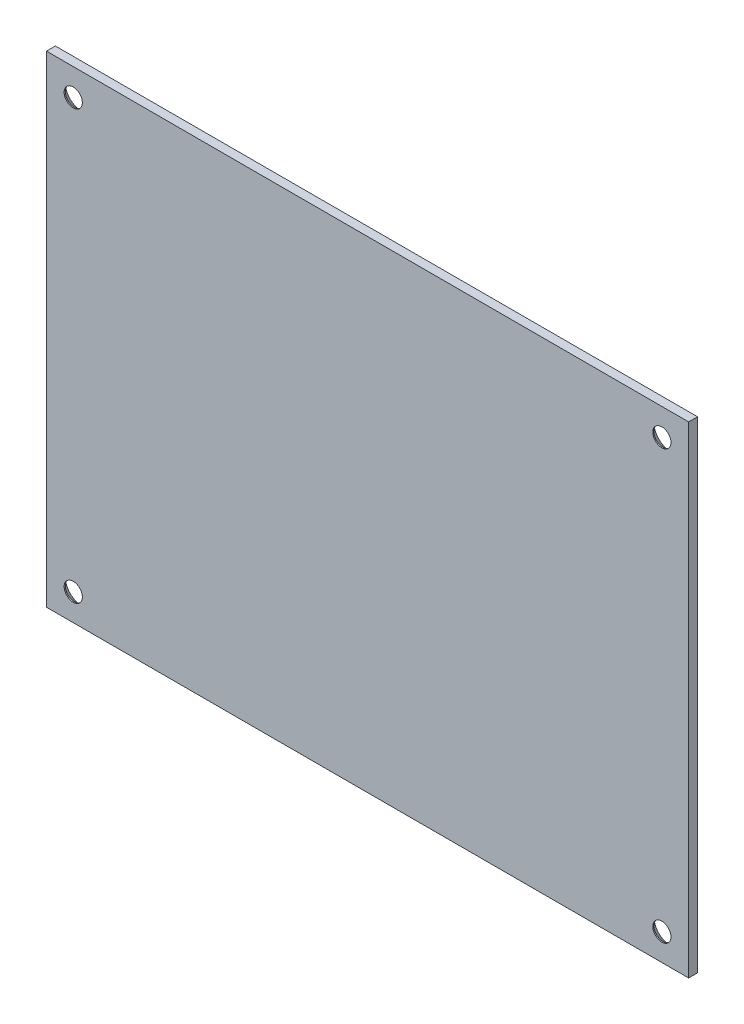
SolidWorks part; units mm, degrees
ref_plane "Front Plane" through (0, 0, 0) normal (0, 0, 1) x (1, 0, 0)
ref_plane "Top Plane" through (0, 0, 0) normal (0, 1, 0) x (1, 0, 0)
ref_plane "Right Plane" through (0, 0, 0) normal (1, 0, 0) x (0, 0, -1)
sketch "Sketch1" plane through (0, 0, 0) normal (0, 0, 1) x (1, 0, 0)
  line L1 (0, 0) -> (120, 0)
  line L2 (0, 0) -> (0, 90)
  line L3 (0, 90) -> (120, 90)
  line L4 (120, 0) -> (120, 90)
  dimension "D1" = 120
  dimension "D2" = 90
extrude "Boss-Extrude1" add sketch "Sketch1" along normal blind 1.66
sketch "Sketch3" plane through (0, 0, 0) normal (0, 0, -1) x (-1, 0, 0)
  line L8 (-5, 5) -> (-5, 85)
  line L9 (-5, 85) -> (-115, 85)
  line L10 (-115, 85) -> (-115, 5)
  line L11 (-115, 5) -> (-5, 5)
  line L12 (-5, 5) -> (-5, 85)
  line L13 (-5, 85) -> (-115, 85)
  line L14 (-115, 85) -> (-115, 5)
  line L15 (-115, 5) -> (-5, 5)
  point P6 (-5, 5)
  point P8 (-5, 85)
  point P10 (-115, 85)
  point P11 (-115, 5)
  dimension "D1" = 5
hole_wizard "CSK for M3 Countersunk Flat Head Screw1" positions "Sketch3" profile "Sketch4" countersink size "M3" standard "ISO"
sketch "Sketch4" plane through (5, 5, 0) normal (1, 0, 0) x (0, 1, 0)
  line L0 (0, 0) -> (0, 31.0215)
  line L1 (0, 31.0215) -> (1.7, 30)
  line L2 (1.7, 30) -> (1.7, 1.45)
  line L3 (1.7, 1.45) -> (3.15, 0)
  line L5 (3.15, 0) -> (0, 0)
  line L6 (-1.7, 1.45) -> (-3.15, 0) construction
  line L10 (0, 31.0215) -> (-1.7, 30) construction
  line L11 (0, -6.35) -> (0, 107.95) construction
  dimension "Hole Dia." = 3.4
  dimension "Hole Depth" = 30
  dimension "Near C'Sink Dia." = 6.3
  dimension "Near C'Sink Angle" = 90
  dimension "Drill Angle" = 118
